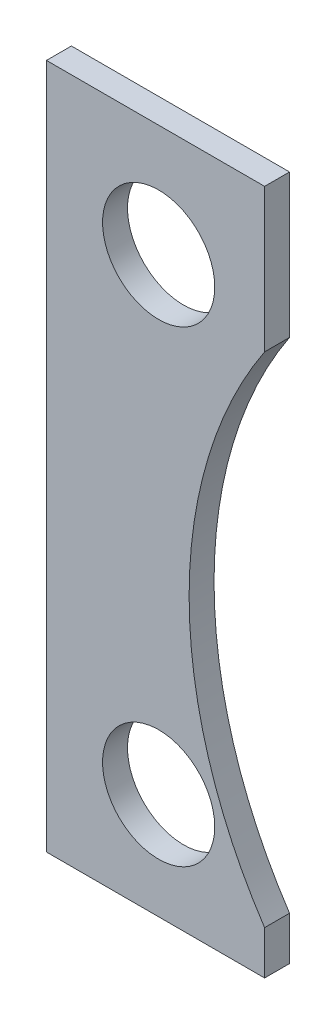
SolidWorks part; units mm, degrees
ref_plane "Ön Düzlem" through (0, 0, 0) normal (0, 0, 1) x (1, 0, 0)
ref_plane "Üst Düzlem" through (0, 0, 0) normal (0, 1, 0) x (1, 0, 0)
ref_plane "Sağ Düzlem" through (0, 0, 0) normal (1, 0, 0) x (0, 0, -1)
sketch "Sketch1" plane through (0, 0, 0) normal (0, 0, 1) x (1, 0, 0)
  line L0 (0, 110) -> (35, 110)
  line L1 (0, 110) -> (0, 0)
  line L2 (0, 0) -> (35, 0)
  line L3 (35, 110) -> (35, 87)
  line L4 (35, 7) -> (35, 0)
  arc A0 (35, 87) -> (35, 7) centre (95, 47) ccw
  dimension "D1" = 110
  dimension "D2" = 35
  dimension "D3" = 7
  dimension "D4" = 23
  dimension "D5" = 95
extrude "Boss-Extrude1" add sketch "Sketch1" along normal mid plane 4
sketch "Sketch2" plane through (0, 0, 2) normal (0, 0, 1) x (1, 0, 0)
  circle A0 centre (18, 92) radius 9
  circle A1 centre (18, 17) radius 9
extrude "Cut-Extrude1" cut sketch "Sketch2" against normal through all
